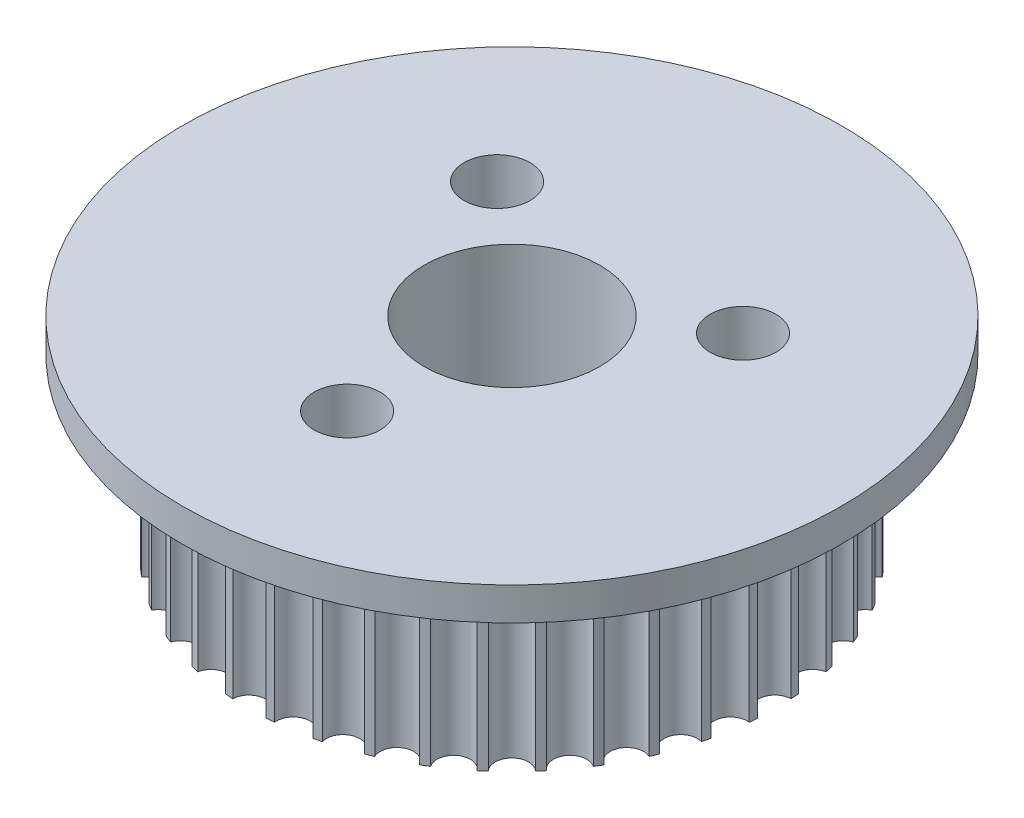
SolidWorks part; units mm, degrees
material "ABS"
ref_plane "Front Plane" through (0, 0, 0) normal (0, 0, 1) x (1, 0, 0)
ref_plane "Top Plane" through (0, 0, 0) normal (0, 1, 0) x (1, 0, 0)
ref_plane "Right Plane" through (0, 0, 0) normal (1, 0, 0) x (0, 0, -1)
sketch "Sketch1" plane through (0, 0, 0) normal (0, 1, 0) x (1, 0, 0)
  arc A0 (-2.619, 11.68) -> (-2.969, 11.5959) centre (0, 0) ccw
  arc A1 (-0.7596, 11.9459) -> (0.7596, 11.9459) centre (0, 11.97) ccw
  arc A2 (1.1185, 11.9176) -> (2.619, 11.68) centre (1.8725, 11.8226) ccw
  arc A3 (2.969, 11.5959) -> (4.4139, 11.1265) centre (3.6989, 11.3841) ccw
  arc A4 (4.7465, 10.9887) -> (6.1001, 10.299) centre (5.4343, 10.6653) ccw
  arc A5 (6.4071, 10.1109) -> (7.6362, 9.2179) centre (7.0358, 9.6839) ccw
  arc A6 (7.9099, 8.9841) -> (8.9841, 7.9099) centre (8.4641, 8.4641) ccw
  arc A7 (9.2179, 7.6362) -> (10.1109, 6.4071) centre (9.6839, 7.0358) ccw
  arc A8 (10.299, 6.1001) -> (10.9887, 4.7465) centre (10.6653, 5.4343) ccw
  arc A9 (11.1265, 4.4139) -> (11.5959, 2.969) centre (11.3841, 3.6989) ccw
  arc A10 (11.68, 2.619) -> (11.9176, 1.1185) centre (11.8226, 1.8725) ccw
  arc A11 (11.9459, 0.7596) -> (11.9459, -0.7596) centre (11.97, 0) ccw
  arc A12 (11.9176, -1.1185) -> (11.68, -2.619) centre (11.8226, -1.8725) ccw
  arc A13 (11.5959, -2.969) -> (11.1265, -4.4139) centre (11.3841, -3.6989) ccw
  arc A14 (10.9887, -4.7465) -> (10.299, -6.1001) centre (10.6653, -5.4343) ccw
  arc A15 (10.1109, -6.4071) -> (9.2179, -7.6362) centre (9.6839, -7.0358) ccw
  arc A16 (8.9841, -7.9099) -> (7.9099, -8.9841) centre (8.4641, -8.4641) ccw
  arc A17 (7.6362, -9.2179) -> (6.4071, -10.1109) centre (7.0358, -9.6839) ccw
  arc A18 (6.1001, -10.299) -> (4.7465, -10.9887) centre (5.4343, -10.6653) ccw
  arc A19 (4.4139, -11.1265) -> (2.969, -11.5959) centre (3.6989, -11.3841) ccw
  arc A20 (2.619, -11.68) -> (1.1185, -11.9176) centre (1.8725, -11.8226) ccw
  arc A21 (0.7596, -11.9459) -> (-0.7596, -11.9459) centre (0, -11.97) ccw
  arc A22 (-1.1185, -11.9176) -> (-2.619, -11.68) centre (-1.8725, -11.8226) ccw
  arc A23 (-2.969, -11.5959) -> (-4.4139, -11.1265) centre (-3.6989, -11.3841) ccw
  arc A24 (-4.7465, -10.9887) -> (-6.1001, -10.299) centre (-5.4343, -10.6653) ccw
  arc A25 (-6.4071, -10.1109) -> (-7.6362, -9.2179) centre (-7.0358, -9.6839) ccw
  arc A26 (-7.9099, -8.9841) -> (-8.9841, -7.9099) centre (-8.4641, -8.4641) ccw
  arc A27 (-9.2179, -7.6362) -> (-10.1109, -6.4071) centre (-9.6839, -7.0358) ccw
  arc A28 (-10.299, -6.1001) -> (-10.9887, -4.7465) centre (-10.6653, -5.4343) ccw
  arc A29 (-11.1265, -4.4139) -> (-11.5959, -2.969) centre (-11.3841, -3.6989) ccw
  arc A30 (-11.68, -2.619) -> (-11.9176, -1.1185) centre (-11.8226, -1.8725) ccw
  arc A31 (-11.9459, -0.7596) -> (-11.9459, 0.7596) centre (-11.97, 0) ccw
  arc A32 (-11.9176, 1.1185) -> (-11.68, 2.619) centre (-11.8226, 1.8725) ccw
  arc A33 (-11.5959, 2.969) -> (-11.1265, 4.4139) centre (-11.3841, 3.6989) ccw
  arc A34 (-10.9887, 4.7465) -> (-10.299, 6.1001) centre (-10.6653, 5.4343) ccw
  arc A35 (-10.1109, 6.4071) -> (-9.2179, 7.6362) centre (-9.6839, 7.0358) ccw
  arc A36 (-8.9841, 7.9099) -> (-7.9099, 8.9841) centre (-8.4641, 8.4641) ccw
  arc A37 (-7.6362, 9.2179) -> (-6.4071, 10.1109) centre (-7.0358, 9.6839) ccw
  arc A38 (-6.1001, 10.299) -> (-4.7465, 10.9887) centre (-5.4343, 10.6653) ccw
  arc A39 (-4.4139, 11.1265) -> (-2.969, 11.5959) centre (-3.6989, 11.3841) ccw
  arc A40 (-2.619, 11.68) -> (-1.1185, 11.9176) centre (-1.8725, 11.8226) ccw
  arc A41 (-0.7596, 11.9459) -> (-1.1185, 11.9176) centre (0, 0) ccw
  arc A42 (1.1185, 11.9176) -> (0.7596, 11.9459) centre (0, 0) ccw
  arc A43 (2.969, 11.5959) -> (2.619, 11.68) centre (0, 0) ccw
  arc A44 (4.7465, 10.9887) -> (4.4139, 11.1265) centre (0, 0) ccw
  arc A45 (6.4071, 10.1109) -> (6.1001, 10.299) centre (0, 0) ccw
  arc A46 (7.9099, 8.9841) -> (7.6362, 9.2179) centre (0, 0) ccw
  arc A47 (9.2179, 7.6362) -> (8.9841, 7.9099) centre (0, 0) ccw
  arc A48 (10.299, 6.1001) -> (10.1109, 6.4071) centre (0, 0) ccw
  arc A49 (11.1265, 4.4139) -> (10.9887, 4.7465) centre (0, 0) ccw
  arc A50 (11.68, 2.619) -> (11.5959, 2.969) centre (0, 0) ccw
  arc A51 (11.9459, 0.7596) -> (11.9176, 1.1185) centre (0, 0) ccw
  arc A52 (11.9176, -1.1185) -> (11.9459, -0.7596) centre (0, 0) ccw
  arc A53 (11.5959, -2.969) -> (11.68, -2.619) centre (0, 0) ccw
  arc A54 (10.9887, -4.7465) -> (11.1265, -4.4139) centre (0, 0) ccw
  arc A55 (10.1109, -6.4071) -> (10.299, -6.1001) centre (0, 0) ccw
  arc A56 (8.9841, -7.9099) -> (9.2179, -7.6362) centre (0, 0) ccw
  arc A57 (7.6362, -9.2179) -> (7.9099, -8.9841) centre (0, 0) ccw
  arc A58 (6.1001, -10.299) -> (6.4071, -10.1109) centre (0, 0) ccw
  arc A59 (4.4139, -11.1265) -> (4.7465, -10.9887) centre (0, 0) ccw
  arc A60 (2.619, -11.68) -> (2.969, -11.5959) centre (0, 0) ccw
  arc A61 (0.7596, -11.9459) -> (1.1185, -11.9176) centre (0, 0) ccw
  arc A62 (-1.1185, -11.9176) -> (-0.7596, -11.9459) centre (0, 0) ccw
  arc A63 (-2.969, -11.5959) -> (-2.619, -11.68) centre (0, 0) ccw
  arc A64 (-4.7465, -10.9887) -> (-4.4139, -11.1265) centre (0, 0) ccw
  arc A65 (-6.4071, -10.1109) -> (-6.1001, -10.299) centre (0, 0) ccw
  arc A66 (-7.9099, -8.9841) -> (-7.6362, -9.2179) centre (0, 0) ccw
  arc A67 (-9.2179, -7.6362) -> (-8.9841, -7.9099) centre (0, 0) ccw
  arc A68 (-10.299, -6.1001) -> (-10.1109, -6.4071) centre (0, 0) ccw
  arc A69 (-11.1265, -4.4139) -> (-10.9887, -4.7465) centre (0, 0) ccw
  arc A70 (-11.68, -2.619) -> (-11.5959, -2.969) centre (0, 0) ccw
  arc A71 (-11.9459, -0.7596) -> (-11.9176, -1.1185) centre (0, 0) ccw
  arc A72 (-11.9176, 1.1185) -> (-11.9459, 0.7596) centre (0, 0) ccw
  arc A73 (-11.5959, 2.969) -> (-11.68, 2.619) centre (0, 0) ccw
  arc A74 (-10.9887, 4.7465) -> (-11.1265, 4.4139) centre (0, 0) ccw
  arc A75 (-10.1109, 6.4071) -> (-10.299, 6.1001) centre (0, 0) ccw
  arc A76 (-8.9841, 7.9099) -> (-9.2179, 7.6362) centre (0, 0) ccw
  arc A77 (-7.6362, 9.2179) -> (-7.9099, 8.9841) centre (0, 0) ccw
  arc A78 (-6.1001, 10.299) -> (-6.4071, 10.1109) centre (0, 0) ccw
  arc A79 (-4.4139, 11.1265) -> (-4.7465, 10.9887) centre (0, 0) ccw
  point P86 (0, 0)
  dimension "D1" = 23.94
  dimension "D2" = 1.52
  dimension "D3" = 40
extrude "Boss-Extrude1" add sketch "Sketch1" along normal blind 8
sketch "Sketch2" plane through (0, 8, 0) normal (0, 1, 0) x (1, 0, 0)
  circle A0 centre (0, 0) radius 15
  dimension "D1" = 30
extrude "Boss-Extrude2" add sketch "Sketch2" along normal blind 1.5
sketch "Sketch4" plane through (0, 0, 0) normal (0, -1, 0) x (1, 0, 0)
  line L0 (0, 0) -> (0, 16.9727) construction
  line L1 (0, 0) -> (19.0979, -14.689) construction
  line L2 (0, 0) -> (-15.3755, -13.527) construction
  circle A0 centre (0, 0) radius 4
  circle A2 centre (0, 7.5) radius 1.5
  circle A3 centre (5.9449, -4.5725) radius 1.5
  circle A4 centre (-5.631, -4.954) radius 1.5
  point P4 (-5.631, -4.954)
  point P8 (5.9449, -4.5725)
  point P9 (0, 7.5)
  dimension "D1" = 8
  dimension "D2" = 127.565
  dimension "D3" = 3
  dimension "D4" = 3
  dimension "D5" = 3
  dimension "D6" = 131.34
  dimension "D7" = 101.094
extrude "Cut-Extrude1" cut sketch "Sketch4" against normal blind 23
